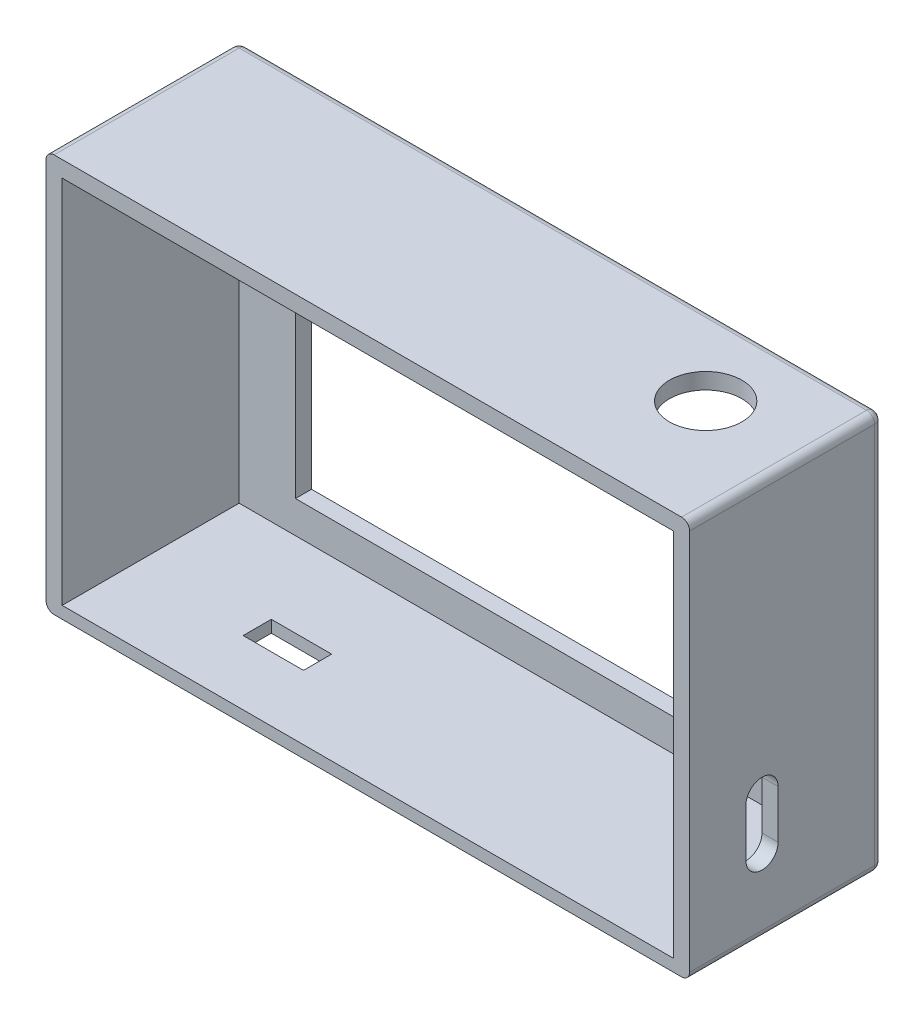
SolidWorks part; units mm, degrees
material "黑"
ref_plane "前视基准面" through (0, 0, 0) normal (0, 0, 1) x (1, 0, 0)
ref_plane "上视基准面" through (0, 0, 0) normal (0, 1, 0) x (1, 0, 0)
ref_plane "右视基准面" through (0, 0, 0) normal (1, 0, 0) x (0, 0, -1)
other "Configuration Table"
sketch "草图1" plane through (0, 0, 0) normal (0, 0, 1) x (1, 0, 0)
  line L1 (-40, 25.75) -> (40, 25.75)
  line L2 (-40, 25.75) -> (-40, -25.75)
  line L3 (-40, -25.75) -> (40, -25.75)
  line L4 (40, 25.75) -> (40, -25.75)
  line L5 (-40, 25.75) -> (40, -25.75) construction
  line L6 (-40, -25.75) -> (40, 25.75) construction
  line L11 (-35.9998, 23.1749) -> (35.431, -22.8087) construction
  line L12 (-35.8699, -22.75) -> (35.8699, 22.75) construction
  line L13 (-38, 25.25) -> (38, 25.25)
  line L14 (-38, 25.25) -> (-38, -25.25)
  line L15 (-38, -25.25) -> (38, -25.25)
  line L16 (38, 25.25) -> (38, -25.25)
  line L17 (-38, 25.25) -> (38, -25.25) construction
  line L18 (-38, -25.25) -> (38, 25.25) construction
  point P0 (0, 0)
  point P6 (0, 0)
  point P14 (0, 0)
  dimension "D1" = 51.5
  dimension "D2" = 80
  dimension "D3" = 0.5
  dimension "D4" = 76
extrude "凸台-拉伸1" add sketch "草图1" along normal blind 22
sketch "草图2" plane through (0, 0, 22) normal (0, 0, 1) x (1, 0, 0)
  line L4 (40, -25.75) -> (40, 25.75)
  line L5 (-40, -25.75) -> (40, -25.75)
  line L6 (-40, 25.75) -> (-40, -25.75)
  line L7 (40, 25.75) -> (-40, 25.75)
  line L8 (40, -25.75) -> (40, 25.75)
  line L9 (-40, -25.75) -> (40, -25.75)
  line L10 (-40, 25.75) -> (-40, -25.75)
  line L11 (40, 25.75) -> (-40, 25.75)
  dimension "D1" = 0
extrude "凸台-拉伸2" add sketch "草图2" against normal blind 2
sketch "草图4" plane through (40, 0, 0) normal (1, 0, 0) x (0, 0, -1)
  line L0 (-13, -11.25) -> (-13, -17.25) construction
  line L1 (-11, -11.25) -> (-11, -17.25)
  line L2 (-15, -11.25) -> (-15, -17.25)
  line L3 (-22, -25.75) -> (-22, 25.75) construction
  line L4 (-22, -25.75) -> (0, -25.75) construction
  arc A0 (-11, -11.25) -> (-15, -11.25) centre (-13, -11.25) ccw
  arc A1 (-15, -17.25) -> (-11, -17.25) centre (-13, -17.25) ccw
  point P2 (-13, -14.25)
  dimension "D2" = 2
  dimension "D1" = 7
  dimension "D3" = 8.5
  dimension "D4" = 6
extrude "切除-拉伸1" cut sketch "草图4" against normal up to next
sketch "草图6" plane through (0, -25.75, 0) normal (0, -1, 0) x (1, 0, 0)
  line L0 (-40, 22) -> (-40, 0) construction
  line L1 (-23.5, 14) -> (-16, 14)
  line L2 (-23.5, 14) -> (-23.5, 10.5)
  line L3 (-23.5, 10.5) -> (-16, 10.5)
  line L4 (-16, 14) -> (-16, 10.5)
  line L6 (-40, 22) -> (40, 22) construction
  dimension "D1" = 16.5
  dimension "D2" = 8
  dimension "D3" = 3.5
  dimension "D4" = 7.5
extrude "切除-拉伸2" cut sketch "草图6" against normal up to next
sketch "草图7" plane through (0, 25.75, 0) normal (0, 1, 0) x (1, 0, 0)
  line L4 (38, -20) -> (38, 0)
  line L5 (-38, -20) -> (38, -20)
  line L6 (-38, 0) -> (-38, -20)
  line L7 (38, 0) -> (-38, 0)
  line L8 (38, -20) -> (38, 0)
  line L9 (-38, -20) -> (38, -20)
  line L10 (-38, 0) -> (-38, -20)
  line L11 (38, 0) -> (-38, 0)
  dimension "D1" = 0
extrude "切除-拉伸3" cut sketch "草图7" against normal up to next
sketch "草图8" plane through (0, 0, 0) normal (0, 0, -1) x (-1, 0, 0)
  line L1 (-40, 25.75) -> (40, 25.75)
  line L2 (-40, 25.75) -> (-40, -25.75)
  line L3 (-40, -25.75) -> (40, -25.75)
  line L4 (40, 25.75) -> (40, -25.75)
  line L5 (-40, 25.75) -> (40, -25.75) construction
  line L6 (-40, -25.75) -> (40, 25.75) construction
  point P0 (0, 0)
extrude "凸台-拉伸3" add sketch "草图8" along normal blind 2
sketch "草图9" plane through (0, 0, -2) normal (0, 0, -1) x (-1, 0, 0)
  line L0 (-31, -19.25) -> (-31, 16.75)
  line L3 (-31, -19.25) -> (31, -19.25)
  line L4 (-31, 16.75) -> (31, 16.75)
  line L5 (31, 16.75) -> (31, -19.25)
  point P0 (0, 0)
  dimension "D1" = 36
  dimension "D2" = 62
extrude "切除-拉伸4" cut sketch "草图9" against normal blind 2
sketch "草图15" plane through (0, -25.75, 0) normal (0, -1, 0) x (1, 0, 0)
  line L4 (-40, 22) -> (-40, -2)
  line L5 (-40, -2) -> (40, -2)
  line L6 (40, -2) -> (40, 22)
  line L7 (40, 22) -> (-40, 22)
  line L8 (-40, 22) -> (-40, -2)
  line L9 (-40, -2) -> (40, -2)
  line L10 (40, -2) -> (40, 22)
  line L11 (40, 22) -> (-40, 22)
  dimension "D1" = 0
extrude "凸台-拉伸5" add sketch "草图15" along normal blind 1
sketch "草图16" plane through (0, -25.75, 0) normal (0, 1, 0) x (1, 0, 0)
  line L4 (-16, -10.5) -> (-23.5, -10.5)
  line L5 (-23.5, -10.5) -> (-23.5, -14)
  line L6 (-23.5, -14) -> (-16, -14)
  line L7 (-16, -14) -> (-16, -10.5)
  line L8 (-16, -10.5) -> (-23.5, -10.5)
  line L9 (-23.5, -10.5) -> (-23.5, -14)
  line L10 (-23.5, -14) -> (-16, -14)
  line L11 (-16, -14) -> (-16, -10.5)
  dimension "D1" = 0
extrude "切除-拉伸6" cut sketch "草图16" against normal blind 1
sketch "草图17" plane through (0, 0, -2) normal (0, 0, -1) x (-1, 0, 0)
  line L1 (-31, -19.25) -> (31, -19.25)
  line L2 (-31, -19.25) -> (-31, -21.25)
  line L3 (-31, -21.25) -> (31, -21.25)
  line L4 (31, -19.25) -> (31, -21.25)
extrude "切除-拉伸7" cut sketch "草图17" against normal blind 2
sketch "草图19" plane through (0, 25.75, 0) normal (0, 1, 0) x (1, 0, 0)
  line L4 (40, -22) -> (40, 2)
  line L5 (40, 2) -> (-40, 2)
  line L6 (-40, 2) -> (-40, -22)
  line L7 (-40, -22) -> (40, -22)
  line L8 (40, -22) -> (40, 2)
  line L9 (40, 2) -> (-40, 2)
  line L10 (-40, 2) -> (-40, -22)
  line L11 (-40, -22) -> (40, -22)
  dimension "D1" = 0
extrude "切除-拉伸8" cut sketch "草图19" against normal blind 3
sketch "草图20" plane through (0, 0, 20) normal (0, 0, -1) x (-1, 0, 0)
  line L0 (38, 22.75) -> (38, -25.25) construction
  line L1 (-38, 22.75) -> (38, 22.75)
  line L2 (-38, 22.75) -> (-38, 20.75)
  line L3 (-38, 20.75) -> (38, 20.75)
  line L4 (38, 22.75) -> (38, 20.75)
extrude "凸台-拉伸6" add sketch "草图20" along normal blind 20
sketch "草图21" plane through (0, 0, 20) normal (0, 0, -1) x (-1, 0, 0)
  line L1 (-38, 20.75) -> (38, 20.75)
  line L2 (-38, 20.75) -> (-38, -25.25)
  line L3 (-38, -25.25) -> (38, -25.25)
  line L4 (38, 20.75) -> (38, -25.25)
extrude "切除-拉伸9" cut sketch "草图21" against normal blind 10
fillet "圆角1" radius 1 8 edges at (40, -26.75, 10) (-40, -26.75, 10) (-40, -2, -2) (40, -2, -2) (0, -26.75, -2) (0, 22.75, -2) (40, 22.75, 10) (-40, 22.75, 10)
sketch "草图22" plane through (0, 22.75, 0) normal (0, 1, 0) x (1, 0, 0)
  line L0 (40, -22) -> (28, -22) construction
  line L1 (-39, -22) -> (39, -22) construction
  line L2 (28, -22) -> (28, -8) construction
  circle A0 centre (28, -8) radius 4.5
extrude "切除-拉伸10" cut sketch "草图22" against normal blind 10 contours A0
sketch "草图23" plane through (0, 0, -2) normal (0, 0, -1) x (-1, 0, 0)
  line L1 (-31, 16.75) -> (31, 16.75)
  line L2 (-31, 16.75) -> (-31, 17.25)
  line L3 (-31, 17.25) -> (31, 17.25)
  line L4 (31, 16.75) -> (31, 17.25)
extrude "切除-拉伸11" cut sketch "草图23" against normal blind 10
